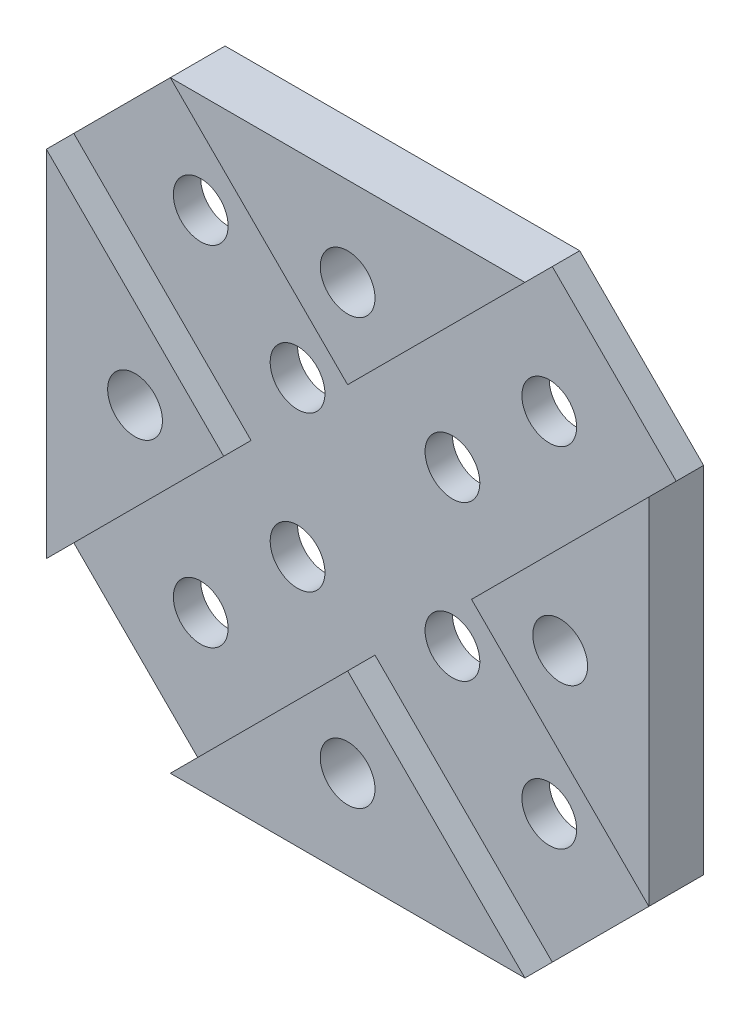
SolidWorks part; units mm, degrees
ref_plane "Plan de face" through (0, 0, 0) normal (0, 0, 1) x (1, 0, 0)
ref_plane "Plan de dessus" through (0, 0, 0) normal (0, 1, 0) x (1, 0, 0)
ref_plane "Plan de droite" through (0, 0, 0) normal (1, 0, 0) x (0, 0, -1)
sketch "Esquisse1" plane through (0, 0, 0) normal (0, 0, 1) x (1, 0, 0)
  line L0 (-55, 32.3726) -> (-32.3726, 55)
  line L1 (55, -55) -> (-55, -55)
  line L2 (55, -55) -> (55, 55)
  line L3 (55, 55) -> (-55, 55)
  line L4 (-55, -55) -> (-55, 55)
  line L5 (55, -55) -> (-55, 55) construction
  line L6 (55, 55) -> (-55, -55) construction
  line L7 (0, -55) -> (0, 55) construction
  line L8 (-55, 0) -> (55, 0) construction
  line L9 (55, 32.3726) -> (32.3726, 55)
  line L10 (55, -32.3726) -> (32.3726, -55)
  line L11 (-55, -32.3726) -> (-32.3726, -55)
  point P0 (0, 0)
  point P23 (0, 0)
  point P26 (0, 0)
  point P29 (0, 0)
  point P32 (0, 0)
  dimension "D2" = 110
  dimension "D3" = 32
  dimension "D4" = 45
  dimension "D7" = 4
extrude "Boss.-Extru.1" add sketch "Esquisse1" along normal blind 10
sketch "Esquisse3" plane through (0, 0, 10) normal (0, 0, 1) x (1, 0, 0)
  line L0 (-55, 32.3726) -> (-32.3726, 55)
  line L1 (-32.3726, 55) -> (0, 22.6274)
  line L2 (55, -32.3726) -> (32.3726, -55)
  line L3 (32.3726, -55) -> (0, -22.6274)
  line L4 (-55, 32.3726) -> (-32.3726, 55) construction
  line L5 (55, -32.3726) -> (32.3726, -55) construction
  line L6 (-55, -32.3726) -> (-32.3726, -55)
  line L7 (-32.3726, -55) -> (0, -22.6274)
  line L9 (32.3726, 55) -> (0, 22.6274)
  line L10 (32.3726, 55) -> (55, 32.3726)
  line L11 (22.6274, 0) -> (55, -32.3726)
  line L12 (-22.6274, 0) -> (-55, -32.3726)
  line L13 (22.6274, 0) -> (55, 32.3726)
  line L14 (-22.6274, 0) -> (-55, 32.3726)
  point P7 (-43.6863, 43.6863)
extrude "Enlèv. mat.-Extru.1" cut sketch "Esquisse3" against normal blind 5
sketch "Esquisse4" plane through (0, 0, 5) normal (0, 0, 1) x (1, 0, 0)
  line L0 (-43.6863, 43.6863) -> (43.6863, -43.6863) construction
  line L1 (-32.3726, 55) -> (-55, 32.3726) construction
  line L2 (32.3726, -55) -> (55, -32.3726) construction
  line L3 (-43.6863, -43.6863) -> (43.6863, 43.6863) construction
  line L4 (-55, -32.3726) -> (-32.3726, -55) construction
  line L5 (55, 32.3726) -> (32.3726, 55) construction
  line L6 (0, 0) -> (-14.1421, 14.1421) construction
  line L7 (0, 0) -> (14.1421, 14.1421) construction
  line L8 (0, 22.6274) -> (0, 55) construction
  line L9 (32.3726, 55) -> (-32.3726, 55) construction
  circle A1 centre (-31.8198, 31.8198) radius 5
  circle A2 centre (-14.1421, 14.1421) radius 5
  circle A3 centre (31.8198, 31.8198) radius 5
  circle A4 centre (14.1421, 14.1421) radius 5
  circle A5 centre (31.8198, -31.8198) radius 5
  circle A6 centre (14.1421, -14.1421) radius 5
  circle A7 centre (-31.8198, -31.8198) radius 5
  circle A8 centre (-14.1421, -14.1421) radius 5
  circle A9 centre (0, 38.8137) radius 5
  circle A10 centre (38.8137, 0) radius 5
  circle A11 centre (0, -38.8137) radius 5
  circle A12 centre (-38.8137, 0) radius 5
  point P49 (0, 0)
  dimension "D1" = 10
  dimension "D2" = 10
  dimension "D7" = 10
  dimension "D3" = 45
  dimension "D4" = 20
  dimension "D6" = 90
  dimension "D5" = 4
  dimension "D8" = 4
extrude "Enlèv. mat.-Extru.2" cut sketch "Esquisse4" against normal through all and the other way through all contours A9
